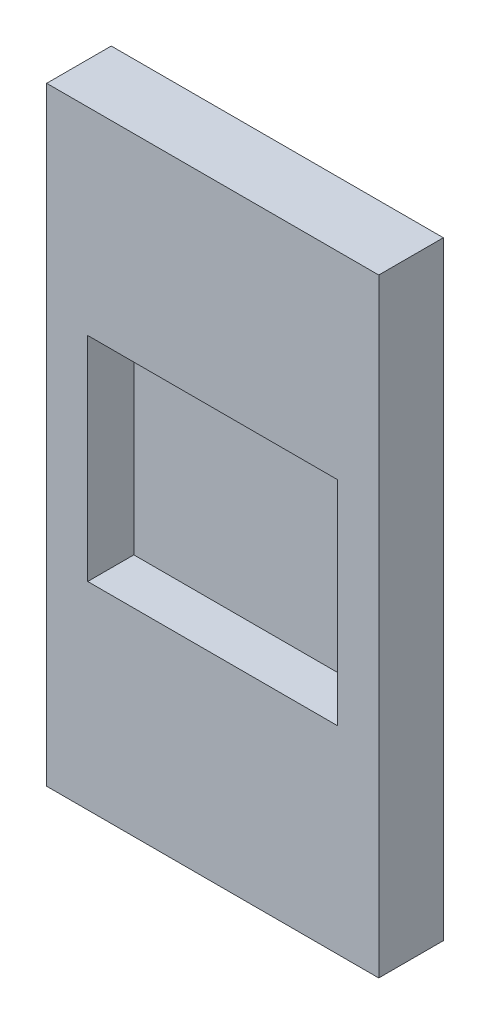
SolidWorks part; units mm, degrees
ref_plane "정면" through (0, 0, 0) normal (0, 0, 1) x (1, 0, 0)
ref_plane "윗면" through (0, 0, 0) normal (0, 1, 0) x (1, 0, 0)
ref_plane "우측면" through (0, 0, 0) normal (1, 0, 0) x (0, 0, -1)
sketch "스케치1" plane through (0, 0, 0) normal (0, 0, 1) x (1, 0, 0)
  line L1 (-9, -16.5) -> (9, -16.5)
  line L2 (-9, -16.5) -> (-9, 16.5)
  line L3 (-9, 16.5) -> (9, 16.5)
  line L4 (9, -16.5) -> (9, 16.5)
  line L5 (-9, -16.5) -> (9, 16.5) construction
  line L6 (-9, 16.5) -> (9, -16.5) construction
  point P0 (0, 0)
  dimension "D1" = 18
  dimension "D2" = 33
extrude "보스-돌출1" add sketch "스케치1" along normal blind 3.5
sketch "스케치2" plane through (0, 0, 3.5) normal (0, 0, 1) x (1, 0, 0)
  line L1 (-6.775, -5.775) -> (6.775, -5.775)
  line L2 (-6.775, -5.775) -> (-6.775, 5.775)
  line L3 (-6.775, 5.775) -> (6.775, 5.775)
  line L4 (6.775, -5.775) -> (6.775, 5.775)
  line L5 (-6.775, -5.775) -> (6.775, 5.775) construction
  line L6 (-6.775, 5.775) -> (6.775, -5.775) construction
  point P1 (0, 0)
  dimension "D1" = 13.55
  dimension "D2" = 11.55
extrude "컷-돌출1" cut sketch "스케치2" against normal blind 2.5
